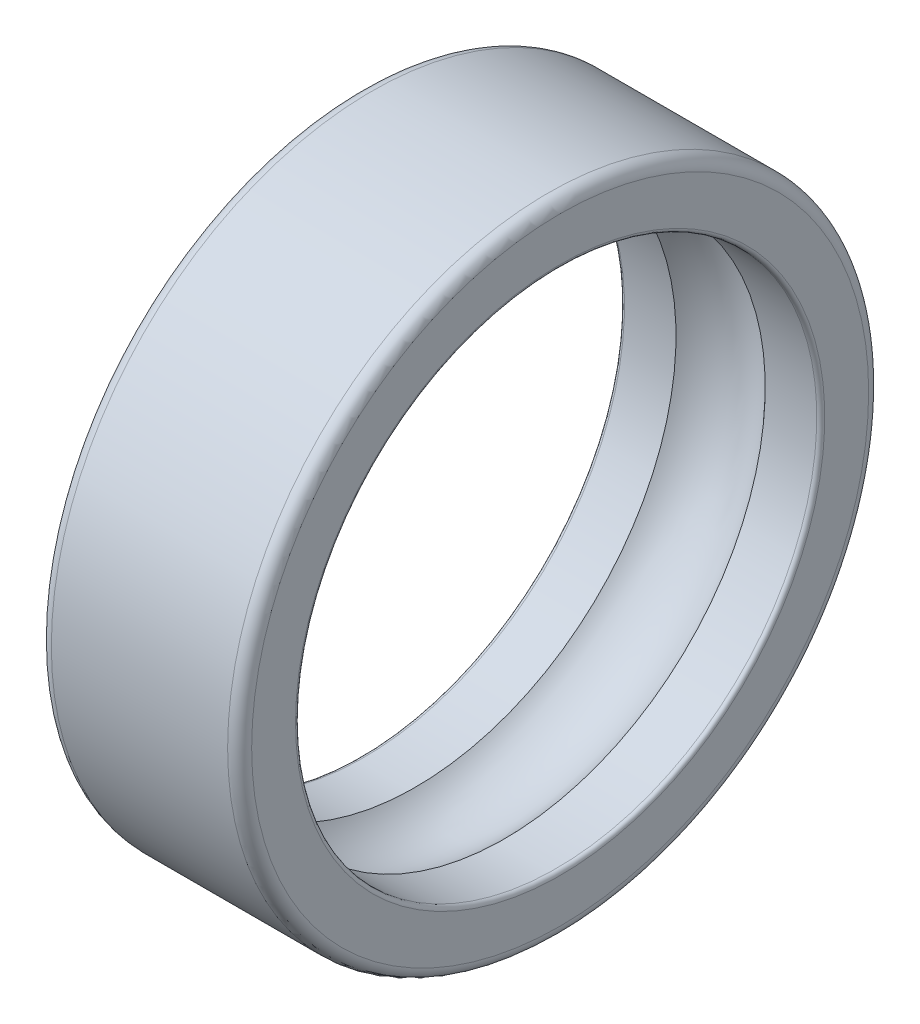
SolidWorks part; units mm, degrees
ref_plane "Plan de face" through (0, 0, 0) normal (0, 0, 1) x (1, 0, 0)
ref_plane "Plan de dessus" through (0, 0, 0) normal (0, 1, 0) x (1, 0, 0)
ref_plane "Plan de droite" through (0, 0, 0) normal (1, 0, 0) x (0, 0, -1)
ref_plane "Plan1" through (0, 0, 0) normal (0, 0, 1) x (1, 0, 0)
sketch "Esquisse1" plane through (0, 0, 0) normal (0, 0, 1) x (1, 0, 0)
  line L0 (0, 15.4) -> (0, 13.21)
  line L1 (0.2, 13.01) -> (2.7729, 13.01)
  line L2 (7.2271, 13.01) -> (9.8, 13.01)
  line L3 (10, 13.21) -> (10, 15.4)
  line L4 (9.4, 16) -> (0.6, 16)
  line L5 (50, 0) -> (-50, 0) construction
  arc A0 (0, 13.21) -> (0.2, 13.01) centre (0.2, 13.21) ccw
  arc A1 (2.7729, 13.01) -> (7.2271, 13.01) centre (5, 11) cw
  arc A2 (9.8, 13.01) -> (10, 13.21) centre (9.8, 13.21) ccw
  arc A3 (10, 15.4) -> (9.4, 16) centre (9.4, 15.4) ccw
  arc A4 (0.6, 16) -> (0, 15.4) centre (0.6, 15.4) ccw
revolve "Révolution1" add sketch "Esquisse1" angle 360 about L5
